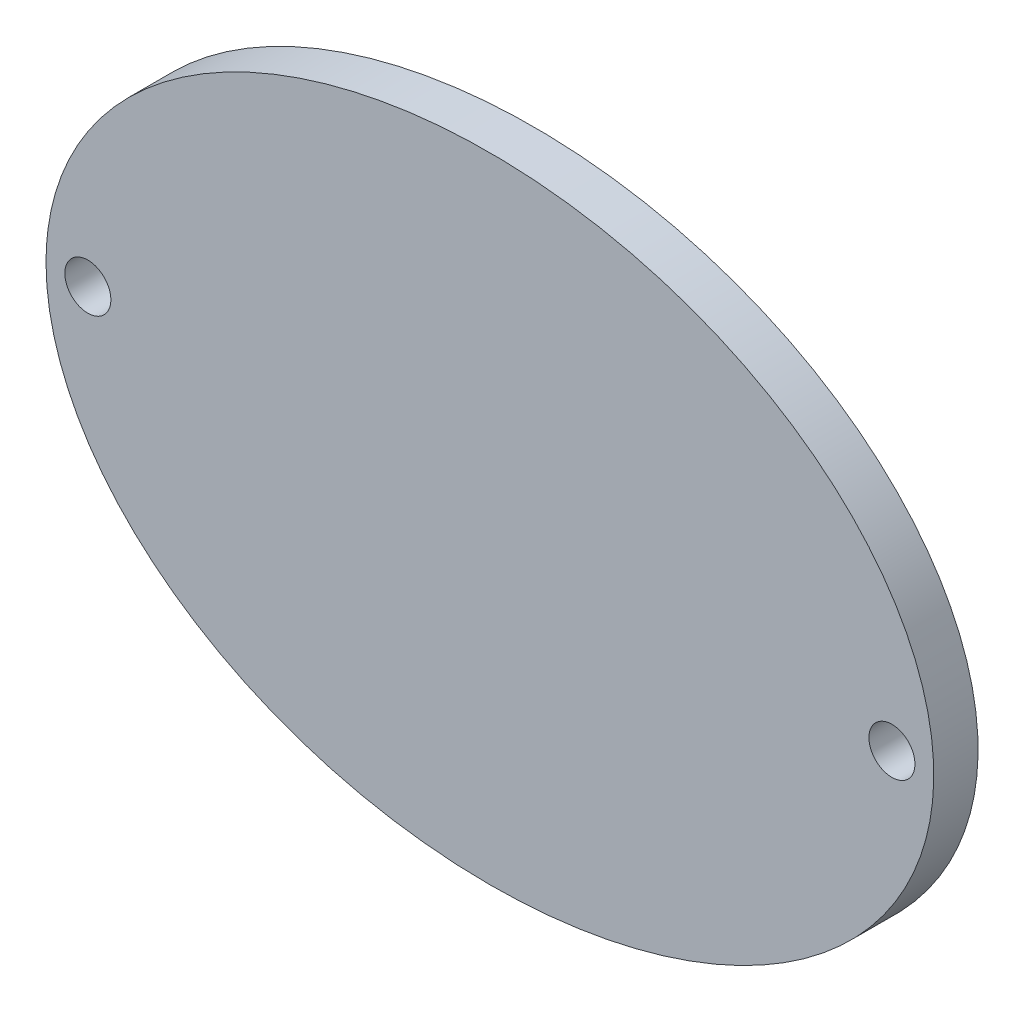
SolidWorks part; units mm, degrees
material "Acrylic (Medium-high impact)"
ref_plane "Plan de face" through (0, 0, 0) normal (0, 0, 1) x (1, 0, 0)
ref_plane "Plan de dessus" through (0, 0, 0) normal (0, 1, 0) x (1, 0, 0)
ref_plane "Plan de droite" through (0, 0, 0) normal (1, 0, 0) x (0, 0, -1)
sketch "Sketch1" plane through (0, 0, 0) normal (0, 0, 1) x (1, 0, 0)
  ellipse E0 centre (0, 0) end of major axis (-31.82, 0) minor radius 22.725
  dimension "D7" = 45.45
  dimension "D8" = 63.64
extrude "Boss-Extrude1" add sketch "Sketch1" along normal blind 3.175
sketch "Sketch2" plane through (0, 0, 3.175) normal (0, 0, 1) x (1, 0, 0)
  line L0 (-31.82, 0) -> (31.82, 0) construction
  line L1 (0, 22.725) -> (0, -22.725) construction
  circle A0 centre (-28.8198, 0) radius 1.65
  circle A1 centre (28.8198, 0) radius 1.65
  ellipse E0 centre (0, 0) end of major axis (-31.82, 0) minor radius 22.725 construction
  dimension "D2" = 3.3
  dimension "D1" = 28.8198
extrude "Cut-Extrude1" cut sketch "Sketch2" against normal through all
